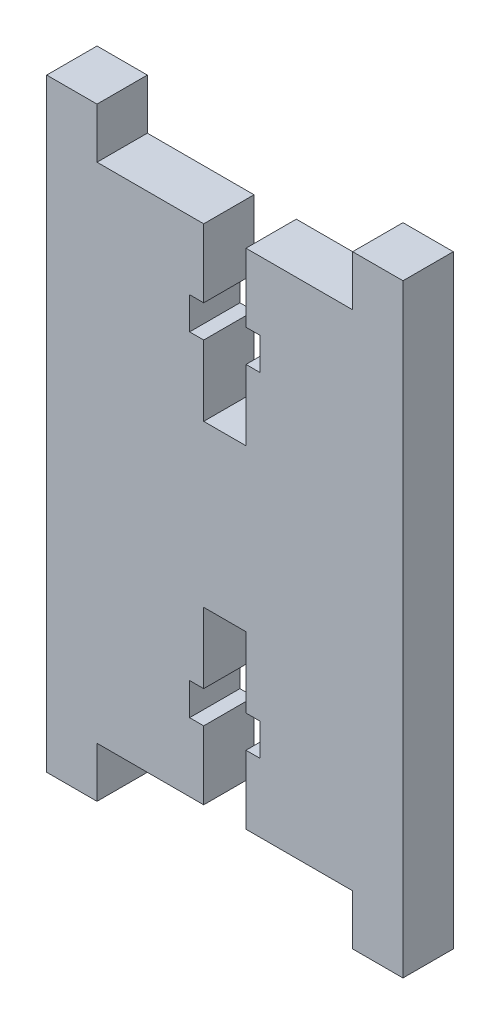
SolidWorks part; units mm, degrees
ref_plane "Front Plane" through (0, 0, 0) normal (0, 0, 1) x (1, 0, 0)
ref_plane "Top Plane" through (0, 0, 0) normal (0, 1, 0) x (1, 0, 0)
ref_plane "Right Plane" through (0, 0, 0) normal (1, 0, 0) x (0, 0, -1)
sketch "Sketch1" plane through (0, 0, 0) normal (0, 0, 1) x (1, 0, 0)
  line L0 (-35.4, 25) -> (-18.4787, 25) construction
  line L1 (-35.4, 50) -> (0, 50)
  line L2 (-35.4, 50) -> (-35.4, 0)
  line L3 (-35.4, 0) -> (0, 0)
  line L4 (0, 50) -> (0, 0)
  line L5 (-35.4, 50) -> (-30.4, 50)
  line L6 (-35.4, 50) -> (-35.4, 55)
  line L7 (-35.4, 55) -> (-30.4, 55)
  line L8 (-30.4, 50) -> (-30.4, 55)
  line L9 (0, 50) -> (-5, 50)
  line L10 (0, 50) -> (0, 55)
  line L11 (0, 55) -> (-5, 55)
  line L12 (-5, 50) -> (-5, 55)
  line L13 (-19.8, 50) -> (-15.6, 50)
  line L14 (-19.8, 50) -> (-19.8, 33)
  line L15 (-19.8, 33) -> (-15.6, 33)
  line L16 (-15.6, 50) -> (-15.6, 33)
  line L17 (-21.2, 43.2) -> (-14.2, 43.2)
  line L18 (-21.2, 43.2) -> (-21.2, 40)
  line L19 (-21.2, 40) -> (-14.2, 40)
  line L20 (-14.2, 43.2) -> (-14.2, 40)
  line L21 (-14.2, 6.8) -> (-14.2, 10)
  line L22 (-21.2, 10) -> (-14.2, 10)
  line L23 (-21.2, 6.8) -> (-21.2, 10)
  line L24 (-21.2, 6.8) -> (-14.2, 6.8)
  line L25 (-15.6, 0) -> (-15.6, 17)
  line L26 (-19.8, 17) -> (-15.6, 17)
  line L27 (-19.8, 0) -> (-19.8, 17)
  line L28 (-19.8, 0) -> (-15.6, 0)
  line L29 (-5, 0) -> (-5, -5)
  line L30 (0, -5) -> (-5, -5)
  line L31 (0, 0) -> (0, -5)
  line L32 (0, 0) -> (-5, 0)
  line L33 (-30.4, 0) -> (-30.4, -5)
  line L34 (-35.4, -5) -> (-30.4, -5)
  line L35 (-35.4, 0) -> (-35.4, -5)
  line L36 (-35.4, 0) -> (-30.4, 0)
  point P19 (-17.7, 33)
  point P20 (-17.7, 40)
  point P21 (-17.7, 50)
  dimension "D1" = 50
  dimension "D2" = 35.4
  dimension "D3" = 5
  dimension "D4" = 5
  dimension "D5" = 5
  dimension "D6" = 5
  dimension "D7" = 4.2
  dimension "D8" = 6.8
  dimension "D9" = 3.2
  dimension "D10" = 7
  dimension "D11" = 17
extrude "Boss-Extrude1" add sketch "Sketch1" along normal blind 5
